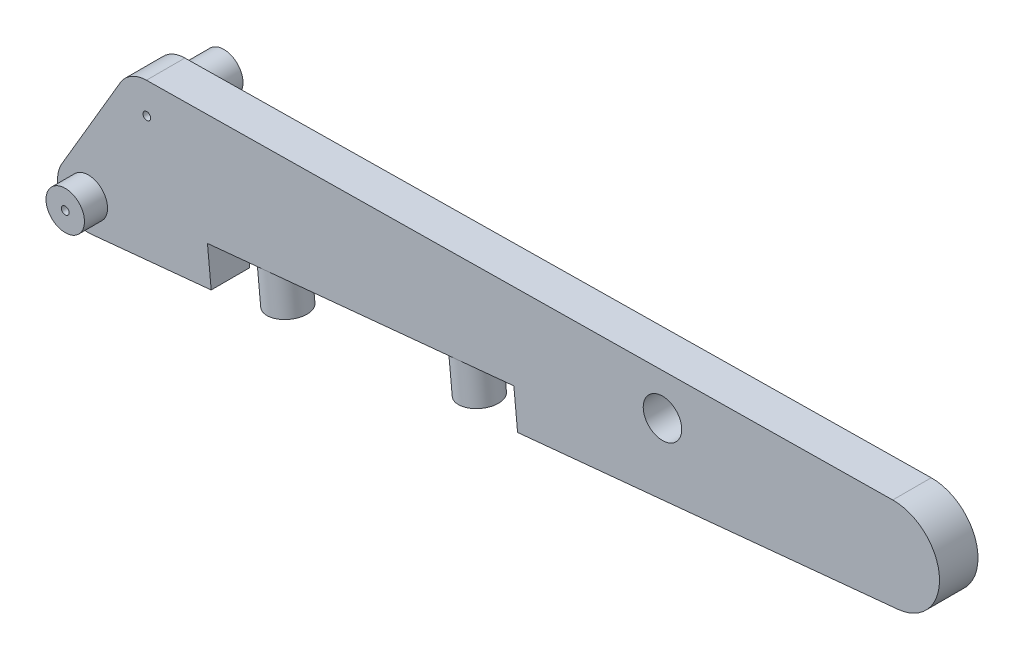
SolidWorks part; units mm, degrees
material "ABS"
ref_plane "Front Plane" through (0, 0, 0) normal (0, 0, 1) x (1, 0, 0)
ref_plane "Top Plane" through (0, 0, 0) normal (0, 1, 0) x (1, 0, 0)
ref_plane "Right Plane" through (0, 0, 0) normal (1, 0, 0) x (0, 0, -1)
sketch "Sketch2" plane through (0, 0, 0) normal (0, 0, 1) x (1, 0, 0)
  line L0 (-7.5998, -12.9323) -> (0, 0)
  line L1 (0, 0) -> (97, -0.7468)
  dimension "D1" = 97
  dimension "D2" = 15
  dimension "D3" = 120
sketch "Sketch3" plane through (0, 0, 0) normal (0, 0, 1) x (1, 0, 0)
  line L0 (-11.0484, -10.9056) -> (-3.4486, 2.0266)
  line L1 (-0.0517, 3.9997) -> (96.9225, 5.2527)
  line L2 (97.581, -6.7186) -> (-7.2125, -16.9135)
  circle A0 centre (-7.5998, -12.9323) radius 2.5
  arc A1 (-11.0484, -10.9056) -> (-7.2125, -16.9135) centre (-7.5998, -12.9323) ccw
  circle A2 centre (0, 0) radius 2.5
  arc A3 (-0.0517, 3.9997) -> (-3.4486, 2.0266) centre (0, 0) ccw
  arc A4 (97.581, -6.7186) -> (96.9225, 5.2527) centre (97, -0.7468) ccw
  dimension "D1" = 5
  dimension "D2" = 8
  dimension "D3" = 5
  dimension "D4" = 8
  dimension "D5" = 12
extrude "Boss-Extrude1" add sketch "Sketch3" along normal blind 5
sketch "Sketch4" plane through (0, 0, 5) normal (0, 0, 1) x (1, 0, 0)
  circle A0 centre (0, 0) radius 2.5
  circle A1 centre (0, 0) radius 0.5
  dimension "D1" = 1
  dimension "D2" = 5
extrude "Boss-Extrude2" add sketch "Sketch4" against normal blind 10
sketch "Sketch5" plane through (0, 0, 0) normal (0, 0, -1) x (-1, 0, 0)
  circle A0 centre (7.5998, -12.9323) radius 2.5
  circle A1 centre (7.5998, -12.9323) radius 0.5
  dimension "D1" = 1
  dimension "D2" = 5
extrude "Boss-Extrude3" add sketch "Sketch5" against normal blind 8
sketch "Sketch6" plane through (0, 0, 0) normal (0, 0, -1) x (-1, 0, 0)
  line L0 (0, 0) -> (-97, -0.7468) construction
  circle A1 centre (-67, -0.5158) radius 2.5
  dimension "D1" = 5
  dimension "D2" = 30
extrude "Cut-Extrude1" cut sketch "Sketch6" against normal blind 5
sketch "Sketch7" plane through (0, 0, 0) normal (0, 0, -1) x (-1, 0, 0)
  line L0 (-48.1755, -11.525) -> (-8.3635, -15.3981)
  line L1 (-48.1755, -11.525) -> (-47.6891, -6.525)
  line L2 (-8.3635, -15.3981) -> (-7.877, -10.3981)
  line L3 (-47.6891, -6.525) -> (-7.877, -10.3981)
  line L4 (7.2125, -16.9135) -> (-97.581, -6.7186) construction
  dimension "D1" = 50
  dimension "D2" = 5
  dimension "D3" = 40
extrude "Cut-Extrude2" cut sketch "Sketch7" against normal blind 5
sketch "Sketch8" plane through (1.076, -11.0598, 0) normal (0.0968, -0.9953, 0) x (0.9953, 0.0968, 0)
  line L0 (6.8332, 0) -> (46.8332, 0) construction
  line L1 (46.8332, 5) -> (46.8332, 0) construction
  line L2 (6.8332, 5) -> (6.8332, 0) construction
  circle A0 centre (14.3332, 2.5) radius 2.5
  circle A1 centre (14.3332, 2.5) radius 0.5
  circle A2 centre (39.3332, 2.5) radius 0.5
  circle A3 centre (39.3332, 2.5) radius 2.5
  dimension "D1" = 5
  dimension "D2" = 1
  dimension "D6" = 1
  dimension "D7" = 5
  dimension "D3" = 2.5
  dimension "D4" = 7.5
  dimension "D5" = 2.5
  dimension "D8" = 7.5
extrude "Boss-Extrude4" add sketch "Sketch8" along normal blind 5
